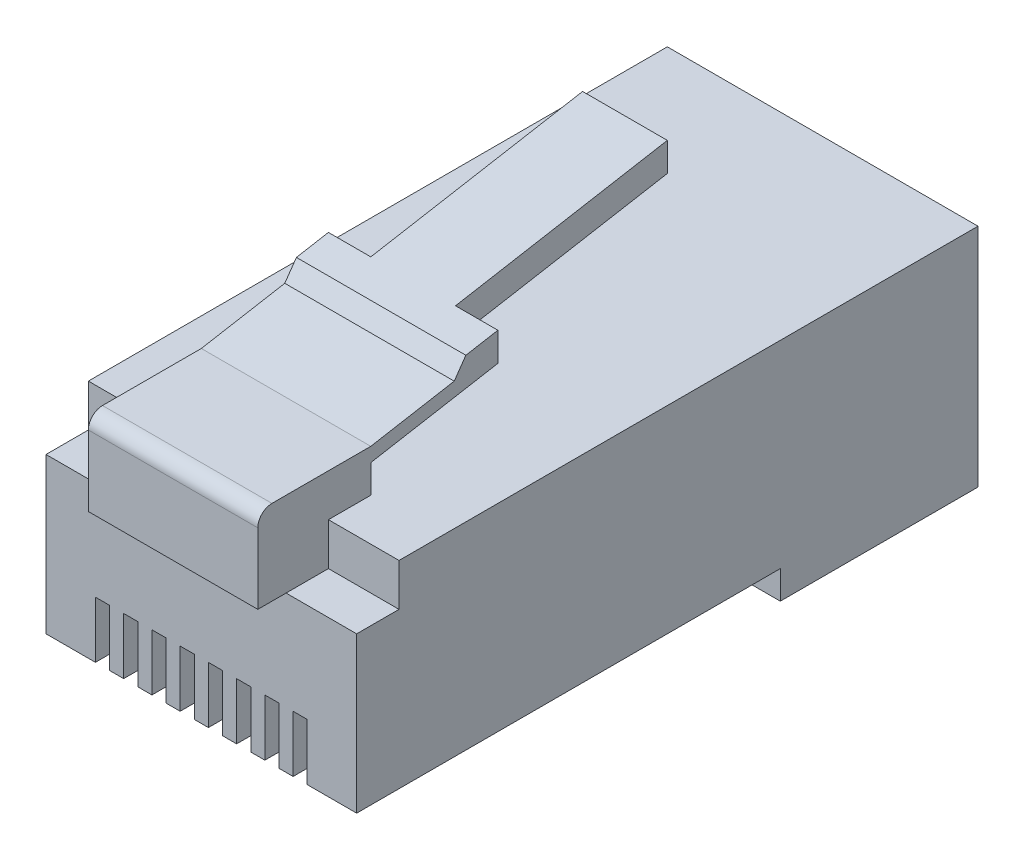
SolidWorks part; units mm, degrees
ref_plane "Piano frontale" through (0, 0, 0) normal (0, 0, 1) x (1, 0, 0)
ref_plane "Piano superiore" through (0, 0, 0) normal (0, 1, 0) x (1, 0, 0)
ref_plane "Piano destro" through (0, 0, 0) normal (1, 0, 0) x (0, 0, -1)
sketch "Schizzo1" plane through (0, 0, 0) normal (0, 0, 1) x (1, 0, 0)
  line L1 (-5.5, 4) -> (5.5, 4)
  line L2 (-5.5, 4) -> (-5.5, -4)
  line L3 (-5.5, -4) -> (5.5, -4)
  line L4 (5.5, 4) -> (5.5, -4)
  line L5 (-5.5, 4) -> (5.5, -4) construction
  line L6 (-5.5, -4) -> (5.5, 4) construction
  point P0 (0, 0)
  dimension "D1" = 11
  dimension "D2" = 8
extrude "Estrusione-Estrusione1" add sketch "Schizzo1" along normal blind 7
sketch "Schizzo2" plane through (0, 0, 7) normal (0, 0, 1) x (1, 0, 0)
  line L0 (5.5, -4) -> (5.5, 4) construction
  line L1 (-5.5, 4) -> (5.5, 4)
  line L2 (-5.5, 4) -> (-5.5, -3)
  line L3 (-5.5, -3) -> (5.5, -3)
  line L4 (5.5, 4) -> (5.5, -3)
  line L5 (-5.5, -4) -> (5.5, -4) construction
  dimension "D1" = 1
extrude "Estrusione-Estrusione2" add sketch "Schizzo2" along normal blind 15
sketch "Schizzo3" plane through (0, 0, 0) normal (0, 0, -1) x (-1, 0, 0)
  line L0 (-4.5, 2.5) -> (-4.5, -2)
  line L1 (-4.5, -2) -> (4.5, -2)
  line L2 (4.5, -2) -> (4.5, 2.5)
  line L3 (5.5, -4) -> (-5.5, -4) construction
  line L4 (5.5, 4) -> (5.5, -4) construction
  line L5 (-5.5, -4) -> (-5.5, 4) construction
  line L6 (-5.5, 4) -> (5.5, 4) construction
  arc A0 (-4.5, 2.5) -> (4.5, 2.5) centre (0, -6.4303) cw
  dimension "D4" = 1.5
  dimension "D5" = 10
  dimension "D1" = 2
  dimension "D2" = 1
  dimension "D3" = 1
extrude "Taglio-Estrusione1" cut sketch "Schizzo3" against normal up to surface (7 mm away) up to face at (-1.375, -3.5, 7)
sketch "Schizzo4" plane through (0, -4, 0) normal (0, -1, 0) x (1, 0, 0)
  line L0 (5.5, 7) -> (5.5, 0) construction
  line L1 (-4.5, 6) -> (4.5, 6)
  line L2 (-4.5, 6) -> (-4.5, 3)
  line L3 (-4.5, 3) -> (4.5, 3)
  line L4 (4.5, 6) -> (4.5, 3)
  line L5 (-4.5, 6) -> (4.5, 3) construction
  line L6 (-4.5, 3) -> (4.5, 6) construction
  line L7 (-5.5, 7) -> (-5.5, 0) construction
  line L8 (-5.5, 7) -> (5.5, 7) construction
  point P0 (0, 4.5)
  dimension "D1" = 1
  dimension "D2" = 1
  dimension "D3" = 3
  dimension "D4" = 1
extrude "Taglio-Estrusione2" cut sketch "Schizzo4" against normal up to surface (2 mm away) up to face at (0, -2, 3.5)
sketch "Schizzo5" plane through (0, 0, 0) normal (1, 0, 0) x (0, 0, -1)
  line L0 (-7, -2) -> (-7, 2.5)
  line L1 (-7, 2.5) -> (-8, 2.5)
  line L2 (-8, 2.5) -> (-8.5, 2)
  line L3 (-8.5, 2) -> (-21.5, 2)
  line L4 (-21.5, 2) -> (-21.5, 1)
  line L5 (-21.5, 1) -> (-12.1962, 1)
  line L6 (-22, 4) -> (0, 4) construction
  line L7 (-22, -3) -> (-7, -3) construction
  line L8 (-22, -3) -> (-22, 4) construction
  line L9 (-7, -4) -> (-7, -3) construction
  line L10 (-9, -3) -> (-9, -1.5)
  line L11 (-9, -1.5) -> (-10, -0.5)
  line L12 (-10, -0.5) -> (-12.5, -0.5)
  line L13 (-12.5, -0.5) -> (-12.5, -3)
  line L14 (-12.5, -3) -> (-9, -3)
  line L16 (-16, -3) -> (-14, -3)
  line L17 (-16, -3) -> (-16, 0)
  line L18 (-16, 0) -> (-14, 0)
  line L19 (-14, -3) -> (-14, 0)
  arc A0 (-12.1962, 1) -> (-7, -2) centre (-12.1962, -5) cw
  dimension "D8" = 6
  dimension "D1" = 1
  dimension "D2" = 1.5
  dimension "D3" = 0.5
  dimension "D4" = 0.5
  dimension "D5" = 1
  dimension "D6" = 1
  dimension "D7" = 0.5
  dimension "D9" = 2.5
  dimension "D10" = 2.5
  dimension "D11" = 2
  dimension "D12" = 1
  dimension "D13" = 1
  dimension "D14" = 2
  dimension "D15" = 1.5
  dimension "D16" = 3
extrude "Taglio-Estrusione3" cut sketch "Schizzo5" against normal up to surface and the other way up to surface up to face at (-4.5, -1.375, 4) other way up to face at (4.5, -1.375, 4)
sketch "Schizzo6" plane through (0, -3, 0) normal (0, -1, 0) x (1, 0, 0)
  line L0 (-5.5, 22) -> (5.5, 22) construction
  line L1 (-3.75, 21.5) -> (-3.25, 21.5)
  line L2 (-3.75, 21.5) -> (-3.75, 18.5)
  line L3 (-3.75, 18.5) -> (-3.25, 18.5)
  line L4 (-3.25, 21.5) -> (-3.25, 18.5)
  line L5 (-2.25, 21.5) -> (-2.25, 18.5)
  line L6 (-2.75, 21.5) -> (-2.75, 18.5)
  line L7 (-2.75, 21.5) -> (-2.25, 21.5)
  line L8 (-2.75, 18.5) -> (-2.25, 18.5)
  line L9 (-1.25, 21.5) -> (-1.25, 18.5)
  line L10 (-1.75, 21.5) -> (-1.75, 18.5)
  line L11 (-1.75, 21.5) -> (-1.25, 21.5)
  line L12 (-1.75, 18.5) -> (-1.25, 18.5)
  line L13 (-0.25, 21.5) -> (-0.25, 18.5)
  line L14 (-0.75, 21.5) -> (-0.75, 18.5)
  line L15 (-0.75, 21.5) -> (-0.25, 21.5)
  line L16 (-0.75, 18.5) -> (-0.25, 18.5)
  line L17 (0.75, 21.5) -> (0.75, 18.5)
  line L18 (0.25, 21.5) -> (0.25, 18.5)
  line L19 (0.25, 21.5) -> (0.75, 21.5)
  line L20 (0.25, 18.5) -> (0.75, 18.5)
  line L21 (1.75, 21.5) -> (1.75, 18.5)
  line L22 (1.25, 21.5) -> (1.25, 18.5)
  line L23 (1.25, 21.5) -> (1.75, 21.5)
  line L24 (1.25, 18.5) -> (1.75, 18.5)
  line L25 (2.75, 21.5) -> (2.75, 18.5)
  line L26 (2.25, 21.5) -> (2.25, 18.5)
  line L27 (2.25, 21.5) -> (2.75, 21.5)
  line L28 (2.25, 18.5) -> (2.75, 18.5)
  line L29 (3.75, 21.5) -> (3.75, 18.5)
  line L30 (3.25, 21.5) -> (3.25, 18.5)
  line L31 (3.25, 21.5) -> (3.75, 21.5)
  line L32 (3.25, 18.5) -> (3.75, 18.5)
  line L33 (5.5, 22) -> (5.5, 7) construction
  dimension "D1" = 0.5
  dimension "D2" = 3
  dimension "D3" = 0.5
  dimension "D5" = 0.5
  dimension "D6" = 1.75
  dimension "D4" = 8
extrude "Taglio-Estrusione4" cut sketch "Schizzo6" against normal up to surface (4 mm away) up to face at (0, 1, 16.8481)
sketch "Schizzo7" plane through (0, -3, 0) normal (0, -1, 0) x (1, 0, 0)
  line L0 (-5.5, 22) -> (5.5, 22) construction
  line L1 (-3.25, 21.5) -> (-3.75, 21.5)
  line L2 (-3.25, 21.5) -> (-3.25, 22)
  line L3 (-3.25, 22) -> (-3.75, 22)
  line L4 (-3.75, 21.5) -> (-3.75, 22)
  line L5 (-2.25, 21.5) -> (-2.25, 22)
  line L6 (-2.25, 21.5) -> (-2.75, 21.5)
  line L7 (-2.75, 21.5) -> (-2.75, 22)
  line L8 (-2.25, 22) -> (-2.75, 22)
  line L9 (-1.25, 21.5) -> (-1.25, 22)
  line L10 (-1.25, 21.5) -> (-1.75, 21.5)
  line L11 (-1.75, 21.5) -> (-1.75, 22)
  line L12 (-1.25, 22) -> (-1.75, 22)
  line L13 (-0.25, 21.5) -> (-0.25, 22)
  line L14 (-0.25, 21.5) -> (-0.75, 21.5)
  line L15 (-0.75, 21.5) -> (-0.75, 22)
  line L16 (-0.25, 22) -> (-0.75, 22)
  line L17 (0.75, 21.5) -> (0.75, 22)
  line L18 (0.75, 21.5) -> (0.25, 21.5)
  line L19 (0.25, 21.5) -> (0.25, 22)
  line L20 (0.75, 22) -> (0.25, 22)
  line L21 (1.75, 21.5) -> (1.75, 22)
  line L22 (1.75, 21.5) -> (1.25, 21.5)
  line L23 (1.25, 21.5) -> (1.25, 22)
  line L24 (1.75, 22) -> (1.25, 22)
  line L25 (2.75, 21.5) -> (2.75, 22)
  line L26 (2.75, 21.5) -> (2.25, 21.5)
  line L27 (2.25, 21.5) -> (2.25, 22)
  line L28 (2.75, 22) -> (2.25, 22)
  line L29 (3.75, 21.5) -> (3.75, 22)
  line L30 (3.75, 21.5) -> (3.25, 21.5)
  line L31 (3.25, 21.5) -> (3.25, 22)
  line L32 (3.75, 22) -> (3.25, 22)
  dimension "D2" = 0.5
  dimension "D1" = 8
extrude "Taglio-Estrusione5" cut sketch "Schizzo7" against normal blind 2
sketch "Schizzo8" plane through (0, 0, 0) normal (1, 0, 0) x (0, 0, -1)
  line L0 (-6, -2) -> (-6, -2.3)
  line L1 (-6, -2) -> (-6, -4) construction
  line L2 (-6, -2.3) -> (-5.0229, -2.5128)
  line L3 (-5.0229, -2.5128) -> (-3.2684, -4)
  line L4 (-6, -4) -> (-3, -4) construction
  line L5 (-3.2684, -4) -> (-3.0311, -2.7854)
  line L6 (-3, -2) -> (-3, -4) construction
  line L7 (-6, -2) -> (-7, -2) construction
  arc A0 (-6, -2) -> (-3.1514, -2.562) centre (-6, -9.5) cw
  arc A1 (-3.0311, -2.7854) -> (-3.1514, -2.562) centre (-3.2274, -2.747) ccw
  point P17 (-3, -2.6261)
  dimension "D4" = 7.5
  dimension "D6" = 0.2
  dimension "D1" = 1
  dimension "D2" = 2.3
  dimension "D3" = 0.3
  dimension "D5" = 152
extrude "Estrusione-Estrusione7" add sketch "Schizzo8" along normal blind 4 and the other way blind 4
sketch "Schizzo9" plane through (0, 1, 0) normal (0, 1, 0) x (1, 0, 0)
  line L0 (-2.75, -18.5) -> (-2.75, -21.5) construction
  line L1 (-3.25, -21.5) -> (-2.75, -21.5)
  line L2 (-3.25, -21.5) -> (-3.25, -14.5)
  line L3 (-3.25, -14.5) -> (-2.75, -14.5)
  line L4 (-2.75, -21.5) -> (-2.75, -14.5)
  line L5 (-1.75, -21.5) -> (-1.75, -14.5)
  line L6 (-2.25, -21.5) -> (-2.25, -14.5)
  line L7 (-2.25, -14.5) -> (-1.75, -14.5)
  line L8 (-2.25, -21.5) -> (-1.75, -21.5)
  line L9 (-0.75, -21.5) -> (-0.75, -14.5)
  line L10 (-1.25, -21.5) -> (-1.25, -14.5)
  line L11 (-1.25, -14.5) -> (-0.75, -14.5)
  line L12 (-1.25, -21.5) -> (-0.75, -21.5)
  line L13 (0.25, -21.5) -> (0.25, -14.5)
  line L14 (-0.25, -21.5) -> (-0.25, -14.5)
  line L15 (-0.25, -14.5) -> (0.25, -14.5)
  line L16 (-0.25, -21.5) -> (0.25, -21.5)
  line L17 (1.25, -21.5) -> (1.25, -14.5)
  line L18 (0.75, -21.5) -> (0.75, -14.5)
  line L19 (0.75, -14.5) -> (1.25, -14.5)
  line L20 (0.75, -21.5) -> (1.25, -21.5)
  line L21 (2.25, -21.5) -> (2.25, -14.5)
  line L22 (1.75, -21.5) -> (1.75, -14.5)
  line L23 (1.75, -14.5) -> (2.25, -14.5)
  line L24 (1.75, -21.5) -> (2.25, -21.5)
  line L25 (3.25, -21.5) -> (3.25, -14.5)
  line L26 (2.75, -21.5) -> (2.75, -14.5)
  line L27 (2.75, -14.5) -> (3.25, -14.5)
  line L28 (2.75, -21.5) -> (3.25, -21.5)
  line L29 (3.75, -21.5) -> (3.75, -18.5) construction
  line L30 (4.5, -21.5) -> (3.75, -21.5)
  line L31 (4.5, -21.5) -> (4.5, -14.5)
  line L32 (4.5, -14.5) -> (3.75, -14.5)
  line L33 (3.75, -21.5) -> (3.75, -14.5)
  line L34 (-4.5, -21.5) -> (-3.75, -21.5)
  line L35 (-4.5, -21.5) -> (-4.5, -14.5)
  line L36 (-4.5, -14.5) -> (-3.75, -14.5)
  line L37 (-3.75, -21.5) -> (-3.75, -14.5)
  line L38 (-3.75, -18.5) -> (-3.75, -21.5) construction
  dimension "D1" = 7
  dimension "D3" = 0.5
  dimension "D2" = 7
extrude "Estrusione-Estrusione8" add sketch "Schizzo9" along normal blind 0.5
fillet "Raccordo1" radius 0.2 16 edges at (-3.25, 1.25, 14.5) (-2.25, 1.25, 14.5) (-1.25, 1.25, 14.5) (-0.25, 1.25, 14.5) (0.75, 1.25, 14.5) (1.75, 1.25, 14.5) (2.75, 1.25, 14.5) (-3.75, 1.25, 14.5) (-2.75, 1.25, 14.5) (-1.75, 1.25, 14.5) (-0.75, 1.25, 14.5) (0.25, 1.25, 14.5) (1.25, 1.25, 14.5) (2.25, 1.25, 14.5) (3.25, 1.25, 14.5) (3.75, 1.25, 14.5)
chamfer "Smusso1" distance 0.2 angle 45 41 edges at (-3.25, 1.5, 18.1) (-3.1914, 1.5, 14.5586) (-3, 1.5, 14.5) (-2.8086, 1.5, 14.5586) (-2.75, 1.5, 18.1) (-2.25, 1.5, 18.1) (-2.1914, 1.5, 14.5586) (-2, 1.5, 14.5) (-1.8086, 1.5, 14.5586) (-1.75, 1.5, 18.1) (-1.25, 1.5, 18.1) (-1.1914, 1.5, 14.5586) (-1, 1.5, 14.5) (-0.8086, 1.5, 14.5586) (-0.75, 1.5, 18.1) (-0.25, 1.5, 18.1) (-0.1914, 1.5, 14.5586) (0, 1.5, 14.5) (0.1914, 1.5, 14.5586) (0.25, 1.5, 18.1) (0.75, 1.5, 18.1) (0.8086, 1.5, 14.5586) (1, 1.5, 14.5) (1.1914, 1.5, 14.5586) (1.25, 1.5, 18.1) (1.75, 1.5, 18.1) (1.8086, 1.5, 14.5586) (2, 1.5, 14.5) (2.1914, 1.5, 14.5586) (2.25, 1.5, 18.1) (2.75, 1.5, 18.1) (2.8086, 1.5, 14.5586) (3, 1.5, 14.5) (3.1914, 1.5, 14.5586) (3.25, 1.5, 18.1) (4.225, 1.5, 14.5) (3.8086, 1.5, 14.5586) (3.75, 1.5, 18.1) (-4.225, 1.5, 14.5) (-3.8086, 1.5, 14.5586) (-3.75, 1.5, 18.1)
sketch "Schizzo10" plane through (5.5, 0, 0) normal (1, 0, 0) x (0, 0, -1)
  line L1 (-22, 4) -> (-20.5, 4)
  line L2 (-22, 4) -> (-22, 2.5)
  line L3 (-22, 2.5) -> (-20.5, 2.5)
  line L4 (-20.5, 4) -> (-20.5, 2.5)
  dimension "D1" = 1.5
  dimension "D2" = 1.5
extrude "Taglio-Estrusione6" cut sketch "Schizzo10" against normal through all
sketch "Schizzo11" plane through (0, 0, 0) normal (1, 0, 0) x (0, 0, -1)
  line L0 (-20.5, 2.5) -> (-23, 2.5)
  line L1 (-23, 2.5) -> (-23, 5)
  line L2 (-22.5, 5.5) -> (-19, 5.5)
  line L3 (-19, 5.5) -> (-16.0456, 6.0209)
  line L4 (-16.0456, 6.0209) -> (-15.6338, 6.609)
  line L5 (-15.6338, 6.609) -> (-7, 8.1314)
  line L6 (-7, 8.1314) -> (-7, 7.1159)
  line L7 (-7, 7.1159) -> (-19, 5)
  line L8 (-19, 5) -> (-19, 4)
  line L9 (-20.5, 4) -> (0, 4) construction
  line L10 (-19, 4) -> (-20.5, 4)
  line L11 (-20.5, 4) -> (-20.5, 2.5)
  line L12 (-22, -3) -> (-22, 2.5) construction
  line L13 (0, -4) -> (0, 4) construction
  arc A0 (-23, 5) -> (-22.5, 5.5) centre (-22.5, 5) cw
  point P21 (-23, 5.5)
  dimension "D11" = 0.5
  dimension "D1" = 3
  dimension "D2" = 4
  dimension "D3" = 1
  dimension "D4" = 170
  dimension "D5" = 1
  dimension "D6" = 45
  dimension "D7" = 1
  dimension "D8" = 7
  dimension "D9" = 1.5
  dimension "D10" = 3
extrude "Estrusione-Estrusione9" add sketch "Schizzo11" along normal blind 3 and the other way blind 3
sketch "Schizzo12" plane through (0, 0, 7) normal (0, 0, -1) x (-1, 0, 0)
  line L1 (3, 5) -> (-3, 5) construction
  line L2 (-3, 8.1314) -> (-1.5, 8.1314)
  line L3 (-3, 8.1314) -> (-3, 5)
  line L4 (-3, 5) -> (-1.5, 5)
  line L6 (-1.5, 8.1314) -> (-1.5, 5)
  line L8 (3, 8.1314) -> (1.5, 8.1314)
  line L9 (3, 8.1314) -> (3, 5)
  line L10 (3, 5) -> (1.5, 5)
  line L11 (1.5, 8.1314) -> (1.5, 5)
  dimension "D1" = 1.5
  dimension "D2" = 1.5
extrude "Taglio-Estrusione7" cut sketch "Schizzo12" against normal blind 7.5
